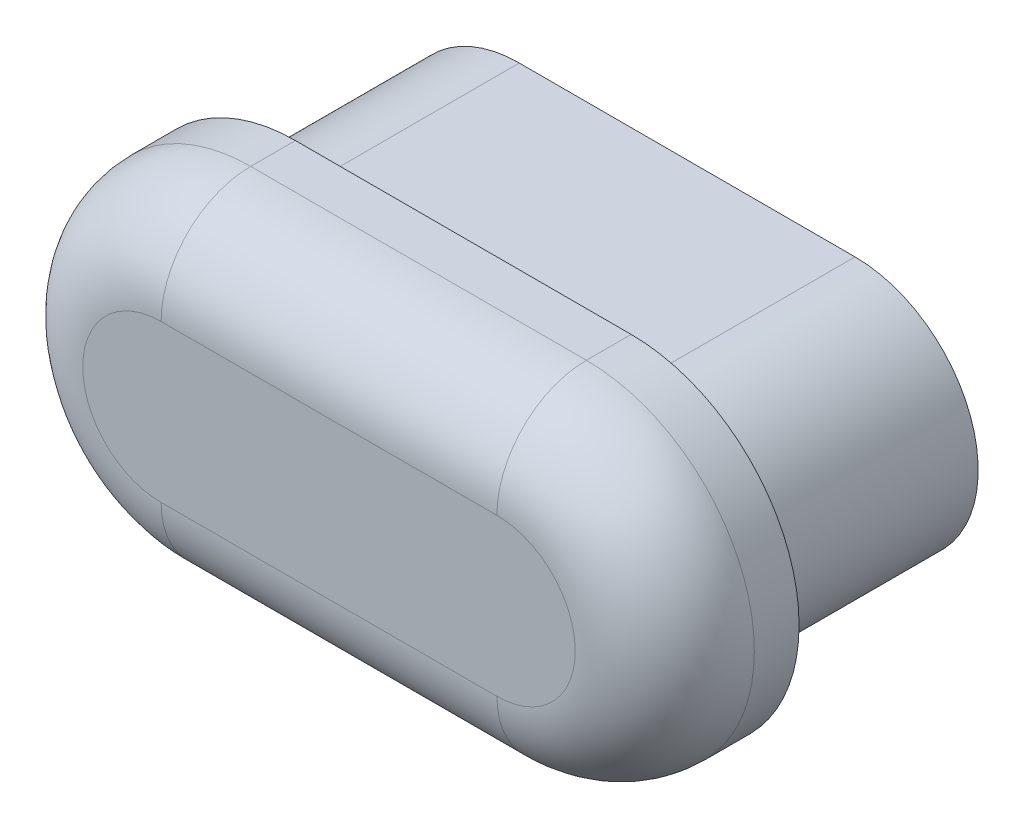
SolidWorks part; units mm, degrees
ref_plane "Спереди" through (0, 0, 0) normal (0, 0, 1) x (1, 0, 0)
ref_plane "Сверху" through (0, 0, 0) normal (0, 1, 0) x (1, 0, 0)
ref_plane "Справа" through (0, 0, 0) normal (1, 0, 0) x (0, 0, -1)
sketch "Эскиз1" plane through (0, 0, 0) normal (0, 0, 1) x (1, 0, 0)
  line L0 (-7.5, 0) -> (7.5, 0) construction
  line L1 (-7.5, 7.5) -> (7.5, 7.5)
  line L2 (-7.5, -7.5) -> (7.5, -7.5)
  arc A0 (-7.5, 7.5) -> (-7.5, -7.5) centre (-7.5, 0) ccw
  arc A1 (7.5, -7.5) -> (7.5, 7.5) centre (7.5, 0) ccw
  point P3 (0, 0)
  dimension "D1" = 15
  dimension "D2" = 30
extrude "Бобышка-Вытянуть1" add sketch "Эскиз1" along normal blind 6
sketch "Эскиз2" plane through (0, 0, 0) normal (0, 0, -1) x (-1, 0, 0)
  line L4 (7.5, 5.5) -> (-7.5, 5.5)
  line L5 (-7.5, -5.5) -> (7.5, -5.5)
  line L6 (7.5, 5.5) -> (-7.5, 5.5)
  line L7 (-7.5, -5.5) -> (7.5, -5.5)
  arc A4 (7.5, -5.5) -> (7.5, 5.5) centre (7.5, 0) ccw
  arc A5 (-7.5, 5.5) -> (-7.5, -5.5) centre (-7.5, 0) ccw
  arc A6 (7.5, -5.5) -> (7.5, 5.5) centre (7.5, 0) ccw
  arc A7 (-7.5, 5.5) -> (-7.5, -5.5) centre (-7.5, 0) ccw
  dimension "D1" = 2
extrude "Бобышка-Вытянуть2" add sketch "Эскиз2" along normal blind 10
fillet "Скругление1" radius 4 4 edges at (0, -7.5, 6) (-15, 0, 6) (0, 7.5, 6) (15, 0, 6)
